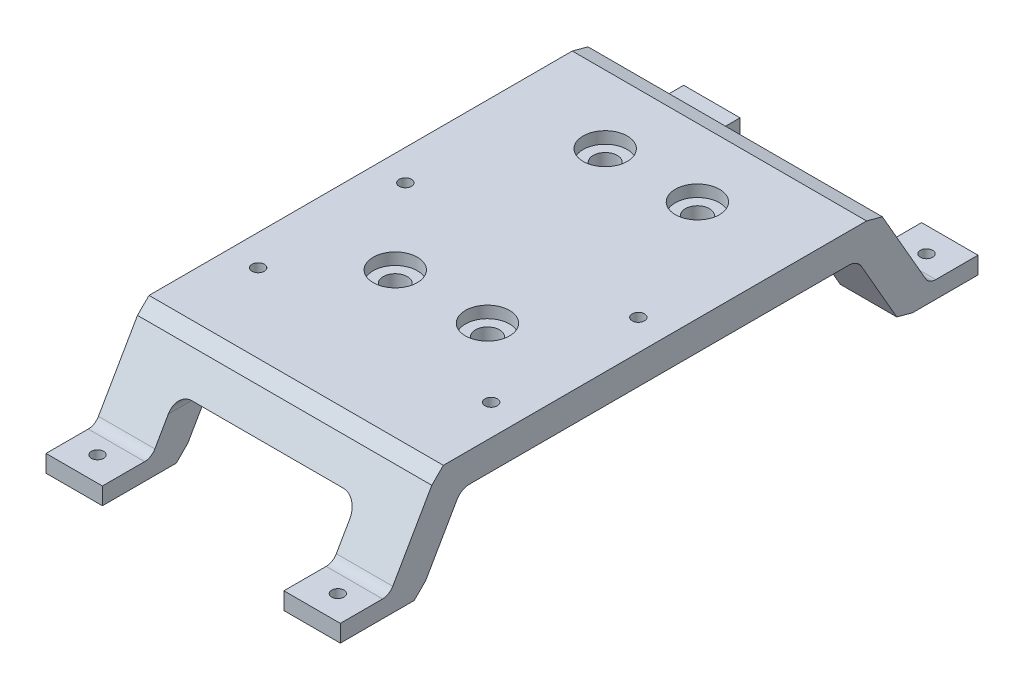
SolidWorks part; units mm, degrees
material "PLA"
ref_plane "Front Plane" through (0, 0, 0) normal (0, 0, 1) x (1, 0, 0)
ref_plane "Top Plane" through (0, 0, 0) normal (0, 1, 0) x (1, 0, 0)
ref_plane "Right Plane" through (0, 0, 0) normal (1, 0, 0) x (0, 0, -1)
sketch "Sketch1" plane through (0, 0, 0) normal (1, 0, 0) x (0, 0, -1)
  line L0 (0, 0) -> (-139.7, 0) construction
  line L1 (0, 0) -> (0, 101.6) construction
  line L2 (-152.4, 0) -> (-132.001, 0)
  line L3 (12.7, 0) -> (12.7, 4.445)
  line L4 (12.7, 4.445) -> (0, 4.445)
  line L5 (0, 4.445) -> (-12.7, 26.543)
  line L6 (-12.7, 26.543) -> (-127, 26.543)
  line L7 (-127, 26.543) -> (-139.7, 4.445)
  line L8 (-139.7, 4.445) -> (-152.4, 4.445)
  line L9 (-152.4, 4.445) -> (-152.4, 0)
  line L10 (-132.001, 0) -> (-121.1257, 18.923)
  line L11 (-121.1257, 18.923) -> (-18.5743, 18.923)
  line L12 (-18.5743, 18.923) -> (-7.699, 0)
  line L13 (-7.699, 0) -> (12.7, 0)
  line L14 (-139.7, 0) -> (-139.7, 4.445) construction
  line L15 (-132.001, 0) -> (-132.001, -19.05) construction
  line L16 (-132.001, -19.05) -> (0, -19.05) construction
  line L17 (0, -19.05) -> (0, 0) construction
  line L18 (-66.0005, -19.05) -> (-66.0005, -45.339) construction
  dimension "D1" = 139.7
  dimension "D2" = 101.6
  dimension "D3" = 4.445
  dimension "D4" = 4.445
  dimension "D5" = 12.7
  dimension "D6" = 12.7
  dimension "D7" = 8.89
  dimension "D8" = 8.89
  dimension "D9" = 7.62
  dimension "D10" = 114.3
  dimension "D11" = 19.05
  dimension "D12" = 26.289
  dimension "D13" = 64.262
extrude "Boss-Extrude1" add sketch "Sketch1" along normal mid plane 76.2
sketch "Sketch2" plane through (0, 18.923, 0) normal (0, -1, 0) x (1, 0, 0)
  line L0 (0, 152.4) -> (0, -12.7) construction
  line L1 (38.1, 152.4) -> (-38.1, 152.4) construction
  line L2 (38.1, -12.7) -> (-38.1, -12.7) construction
  line L3 (-23.876, 60.96) -> (23.876, 60.96) construction
  line L4 (-23.876, 94.107) -> (23.876, 94.107) construction
  line L5 (-23.876, 94.107) -> (-23.876, 27.813) construction
  line L6 (-23.876, 27.813) -> (23.876, 27.813) construction
  line L7 (23.876, 94.107) -> (23.876, 27.813) construction
  line L8 (-23.876, 94.107) -> (23.876, 27.813) construction
  line L9 (-23.876, 27.813) -> (23.876, 94.107) construction
  line L10 (-11.938, 88.138) -> (11.938, 88.138) construction
  circle A0 centre (-11.938, 88.138) radius 3.1115
  circle A1 centre (11.938, 88.138) radius 3.1115
  circle A2 centre (11.938, 33.782) radius 3.1115
  circle A3 centre (-11.938, 33.782) radius 3.1115
  point P6 (0, 60.96)
  point P21 (0, 88.138)
  dimension "D1" = 6.223
  dimension "D2" = 6.223
  dimension "D3" = 23.876
  dimension "D4" = 54.356
  dimension "D5" = 66.294
  dimension "D6" = 47.752
  dimension "D7" = 60.96
extrude "Caster-Mount-Holes" cut sketch "Sketch2" against normal through all
sketch "Sketch6" plane through (0, 4.445, 0) normal (0, 1, 0) x (1, 0, 0)
  line L0 (-38.1, -69.85) -> (38.1, -69.85) construction
  line L1 (-38.1, -12.7) -> (-38.1, -127) construction
  line L2 (38.1, -12.7) -> (38.1, -127) construction
  line L3 (0, 12.7) -> (0, -152.4) construction
  line L4 (38.1, 12.7) -> (-38.1, 12.7) construction
  line L5 (38.1, -152.4) -> (-38.1, -152.4) construction
  circle A0 centre (-31.115, 6.35) radius 1.5875
  circle A1 centre (31.115, 6.35) radius 1.5875
  circle A2 centre (31.115, -146.05) radius 1.5875
  circle A3 centre (-31.115, -146.05) radius 1.5875
  dimension "D2" = 3.175
  dimension "D1" = 6.35
  dimension "D3" = 62.23
extrude "Frame-MountHoles" cut sketch "Sketch6" against normal through all
sketch "Sketch7" plane through (0, 0, -12.7) normal (0, 0, -1) x (-1, 0, 0)
  line L0 (0, 0) -> (0, 26.543) construction
  line L1 (-38.1, 26.543) -> (38.1, 26.543) construction
  line L2 (23.495, 15.875) -> (-23.495, 15.875)
  line L3 (-23.495, 15.875) -> (-23.495, 0)
  line L4 (-38.1, 0) -> (38.1, 0) construction
  line L5 (-23.495, 0) -> (23.495, 0)
  line L6 (23.495, 15.875) -> (23.495, 0)
  point P12 (0, 15.875)
  dimension "D1" = 46.99
  dimension "D2" = 15.875
extrude "Leg-Cutouts" cut sketch "Sketch7" against normal through all
chamfer "Chamfer1" distance 1.27 angle 45 4 edges at (-30.7975, 0, 7.699) (30.7975, 0, 7.699) (-30.7975, 0, 132.001) (30.7975, 0, 132.001)
sketch "Sketch8" plane through (0, 18.923, 0) normal (0, -1, 0) x (1, 0, 0)
  line L0 (0, 0) -> (0, 133.131) construction
  line L1 (-23.495, 133.131) -> (23.495, 133.131) construction
  line L2 (-38.1, 121.1257) -> (-38.1, 18.5743) construction
  line L3 (-38.1, 69.85) -> (38.1, 69.85) construction
  line L4 (38.1, 121.1257) -> (38.1, 18.5743) construction
  line L5 (-30.1625, 105.41) -> (-30.1625, 67.31) construction
  circle A0 centre (-30.1625, 105.41) radius 1.5875
  circle A1 centre (-30.1625, 67.31) radius 1.5875
  circle A2 centre (30.1625, 67.31) radius 1.5875
  circle A3 centre (30.1625, 105.41) radius 1.5875
  point P15 (-30.1625, 86.36)
  dimension "D1" = 3.175
  dimension "D2" = 3.175
  dimension "D3" = 38.1
  dimension "0.4" = 16.51
  dimension "D5" = 60.325
extrude "Electronics-Mount-Holes" cut sketch "Sketch8" against normal through all
chamfer "Chamfer2" distance 1.27 angle 45 2 edges at (0, 26.543, 127) (0, 26.543, 12.7)
fillet "Fillet1" radius 3.81 6 edges at (23.495, 15.875, 11.6958) (-23.495, 15.875, 11.6958) (23.495, 15.875, 128.0042) (-23.495, 15.875, 128.0042) (0, 18.923, 121.1257) (0, 18.923, 18.5743)
fillet "Fillet2" radius 3.048 4 edges at (30.7975, 4.445, 0) (-30.7975, 4.445, 0) (30.7975, 4.445, 139.7) (-30.7975, 4.445, 139.7)
sketch "Sketch9" plane through (0, 26.543, 0) normal (0, 1, 0) x (1, 0, 0)
  circle A0 centre (-11.938, -33.782) radius 5.715
  circle A1 centre (11.938, -33.782) radius 5.715
  circle A2 centre (-11.938, -88.138) radius 5.715
  circle A3 centre (11.938, -88.138) radius 5.715
  dimension "D1" = 11.43
extrude "Cut-Extrude1" cut sketch "Sketch9" against normal blind 3.048
sketch "Sketch10" plane through (0, 18.923, 0) normal (0, -1, 0) x (1, 0, 0)
  circle A0 centre (-30.1625, 105.41) radius 3.175
  circle A1 centre (-30.1625, 67.31) radius 3.175
  circle A2 centre (30.1625, 105.41) radius 3.175
  circle A3 centre (30.1625, 67.31) radius 3.175
  dimension "D1" = 6.35
extrude "Cut-Extrude2" cut sketch "Sketch10" against normal blind 2.159
equation "\"D4@Sketch1\"=\"D3@Sketch1\""
equation "\"D6@Sketch1\"=\"D5@Sketch1\""
equation "\"D8@Sketch1\"=\"D7@Sketch1\""
equation "\"D2@Sketch8\"=\"D1@Sketch8\""
equation "\"D2@Sketch2\"=\"D1@Sketch2\""
